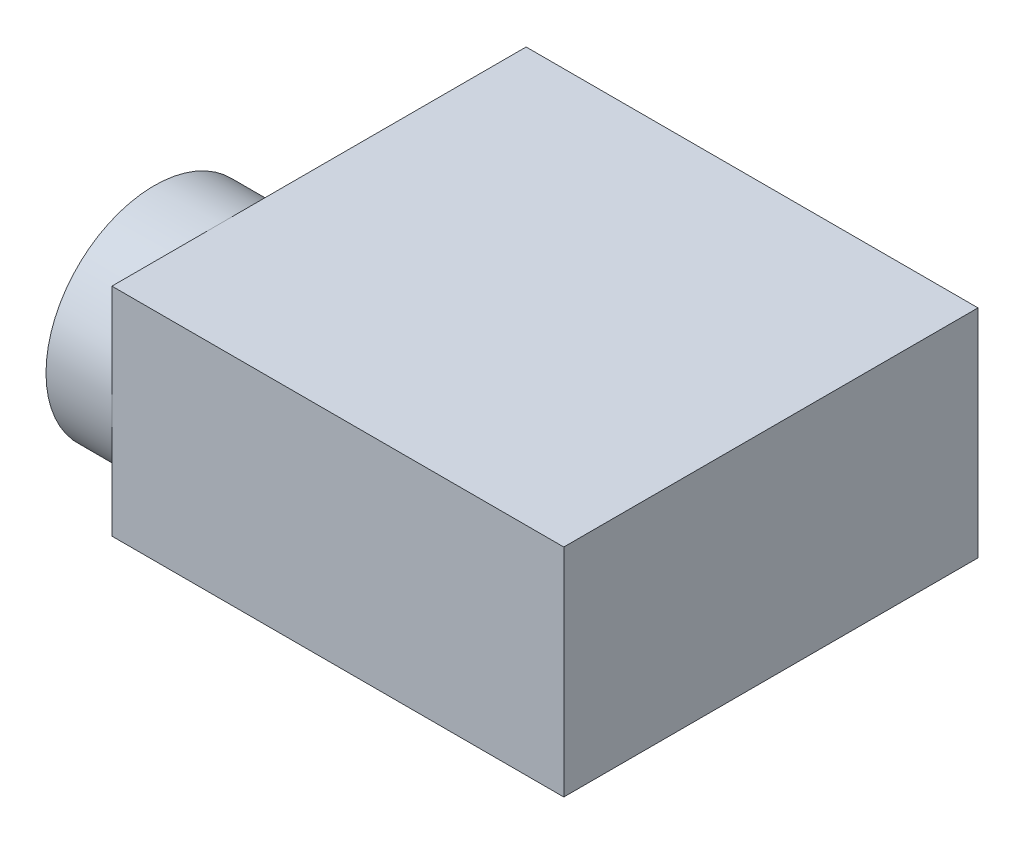
SolidWorks part; units mm, degrees
ref_plane "Front Plane" through (0, 0, 0) normal (0, 0, 1) x (1, 0, 0)
ref_plane "Top Plane" through (0, 0, 0) normal (0, 1, 0) x (1, 0, 0)
ref_plane "Right Plane" through (0, 0, 0) normal (1, 0, 0) x (0, 0, -1)
sketch "Sketch1" plane through (0, 0, 0) normal (0, 1, 0) x (1, 0, 0)
  line L0 (-20, 0) -> (-24, 0)
  line L1 (0, 0) -> (-18, 0)
  line L2 (0, 0) -> (0, 22)
  line L3 (0, 22) -> (-18, 22)
  line L4 (-24, 0) -> (-24, 22)
  line L6 (-20, 0) -> (-20, -4)
  line L7 (-20, -4) -> (-18, -4)
  line L8 (-18, 0) -> (-18, -4)
  line L10 (-20, 22) -> (-20, 26)
  line L11 (-20, 26) -> (-18, 26)
  line L12 (-18, 22) -> (-18, 26)
  line L13 (-20, 22) -> (-24, 22)
  dimension "D1" = 24
  dimension "D2" = 22
  dimension "D3" = 30
  dimension "D4" = 4
  dimension "D5" = 2
extrude "Boss-Extrude1" add sketch "Sketch1" along normal blind 11.5
sketch "Sketch2" plane through (-24, 0, 0) normal (-1, 0, 0) x (0, 0, 1)
  line L1 (-5.75, 5.75) -> (-5.75, 0) construction
  line L2 (-22, 0) -> (0, 0) construction
  line L3 (-5.75, 5.75) -> (-5.75, 11.5) construction
  line L4 (-22, 11.5) -> (0, 11.5) construction
  line L5 (0, 11.5) -> (0, 0) construction
  line L6 (-11.141, 5.75) -> (-5.75, 5.75) construction
  line L7 (-11.141, 3.75) -> (-11.141, 7.75) construction
  arc A0 (-11.141, 3.75) -> (-11.141, 7.75) centre (-5.75, 5.75) ccw
  arc A1 (-11.141, 7.75) -> (-11.141, 3.75) centre (-11.141, 5.75) ccw
  dimension "D1" = 4
extrude "Boss-Extrude2" add sketch "Sketch2" along normal blind 3.5
sketch "Sketch4" plane through (-27.5, 0, 0) normal (-1, 0, 0) x (0, 0, 1)
  circle A0 centre (-5.75, 5.75) radius 1.5
  arc A1 (-11.141, 3.75) -> (-11.141, 7.75) centre (-5.75, 5.75) ccw construction
  dimension "D1" = 3
extrude "Boss-Extrude3" add sketch "Sketch4" along normal blind 3
sketch "Sketch5" plane through (-20, 0, 0) normal (-1, 0, 0) x (0, 0, 1)
  line L2 (-26, 5.75) -> (4.05, 5.75) construction
  line L3 (-26, 11.5) -> (-26, 0) construction
  line L4 (4, 11.5) -> (4, 0) construction
  circle A0 centre (-24.8, 5.75) radius 1.25
  circle A1 centre (2.8, 5.75) radius 1.25
  dimension "D1" = 2.5
  dimension "D2" = 1.2
  dimension "D3" = 1.2
extrude "Cut-Extrude1" cut sketch "Sketch5" against normal blind 3.5
sketch "Sketch6" plane through (-18, 0, 0) normal (1, 0, 0) x (0, 0, -1)
  line L1 (26, 0) -> (22, 0)
  line L2 (26, 0) -> (26, 11.5)
  line L3 (26, 11.5) -> (22, 11.5)
  line L4 (22, 0) -> (22, 11.5)
extrude "Cut-Extrude2" cut sketch "Sketch6" against normal blind 10
sketch "Sketch7" plane through (-18, 0, 0) normal (1, 0, 0) x (0, 0, -1)
  line L1 (-4, 0) -> (0, 0)
  line L2 (-4, 0) -> (-4, 11.5)
  line L3 (-4, 11.5) -> (0, 11.5)
  line L4 (0, 0) -> (0, 11.5)
extrude "Cut-Extrude3" cut sketch "Sketch7" against normal blind 10
